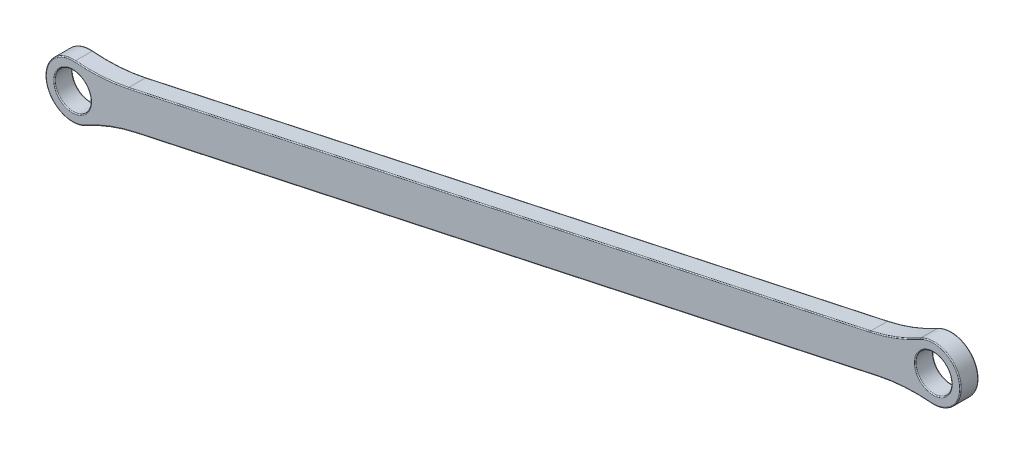
SolidWorks part; units mm, degrees
ref_plane "Front Plane" through (0, 0, 0) normal (0, 0, 1) x (1, 0, 0)
ref_plane "Top Plane" through (0, 0, 0) normal (0, 1, 0) x (1, 0, 0)
ref_plane "Right Plane" through (0, 0, 0) normal (1, 0, 0) x (0, 0, -1)
sketch "Sketch1" plane through (0, 0, 0) normal (0, 0, 1) x (1, 0, 0)
  line L0 (-68.3427, 229.2077) -> (-211.0537, 198.3926) construction
  line L1 (-68.3427, 229.2077) -> (-211.0537, 198.3926) construction
  line L2 (-211.0537, 198.3926) -> (-68.3427, 229.2077) construction
  line L3 (-211.6869, 201.325) -> (-68.9759, 232.1401)
  line L4 (-210.4205, 195.4601) -> (-67.7095, 226.2753)
  arc A0 (-211.6869, 201.325) -> (-210.4205, 195.4601) centre (-211.0537, 198.3926) ccw
  arc A1 (-67.7095, 226.2753) -> (-68.9759, 232.1401) centre (-68.3427, 229.2077) ccw
  circle A2 centre (-211.0537, 198.3926) radius 4.5
  circle A3 centre (-68.3427, 229.2077) radius 4.5
  arc A4 (-211.6869, 201.325) -> (-210.4205, 195.4601) centre (-211.0537, 198.3926) cw
  arc A5 (-68.9759, 232.1401) -> (-67.7095, 226.2753) centre (-68.3427, 229.2077) ccw
  point P3 (-139.6982, 213.8001)
  dimension "D2" = 9
  dimension "D1" = 6
  dimension "D3" = 146
extrude "Boss-Extrude1" add sketch "Sketch1" against normal blind 3 contours L3 A2 L4 A0 | A3 L3 A2 L4 | L3 A4 L4 A2 | L4 A3 L3 A1 | A5 L3 A3 L4
fillet "Fillet1" radius 30 4 edges at (-207.142, 196.1681, -1.5) (-70.9881, 225.5674, -1.5) (-208.4084, 202.0329, -1.5) (-72.2545, 231.4322, -1.5)
fillet "Fillet2" radius 0.15 20 edges at (-208.0537, 198.3926, -3) (-208.0537, 198.3926, 0) (-204.8393, 196.3298, -3) (-204.8393, 196.3298, 0) (-139.065, 210.8677, 0) (-139.065, 210.8677, -3) (-73.1523, 224.7646, -3) (-73.1523, 224.7646, 0) (-63.9441, 230.1575, 0) (-63.9441, 230.1575, -3) (-74.5571, 231.2704, -3) (-74.5571, 231.2704, 0) (-140.3314, 216.7326, -3) (-140.3314, 216.7326, 0) (-206.2441, 202.8357, -3) (-206.2441, 202.8357, 0) (-215.4523, 197.4428, -3) (-215.4523, 197.4428, 0) (-65.3427, 229.2077, -3) (-65.3427, 229.2077, 0)
